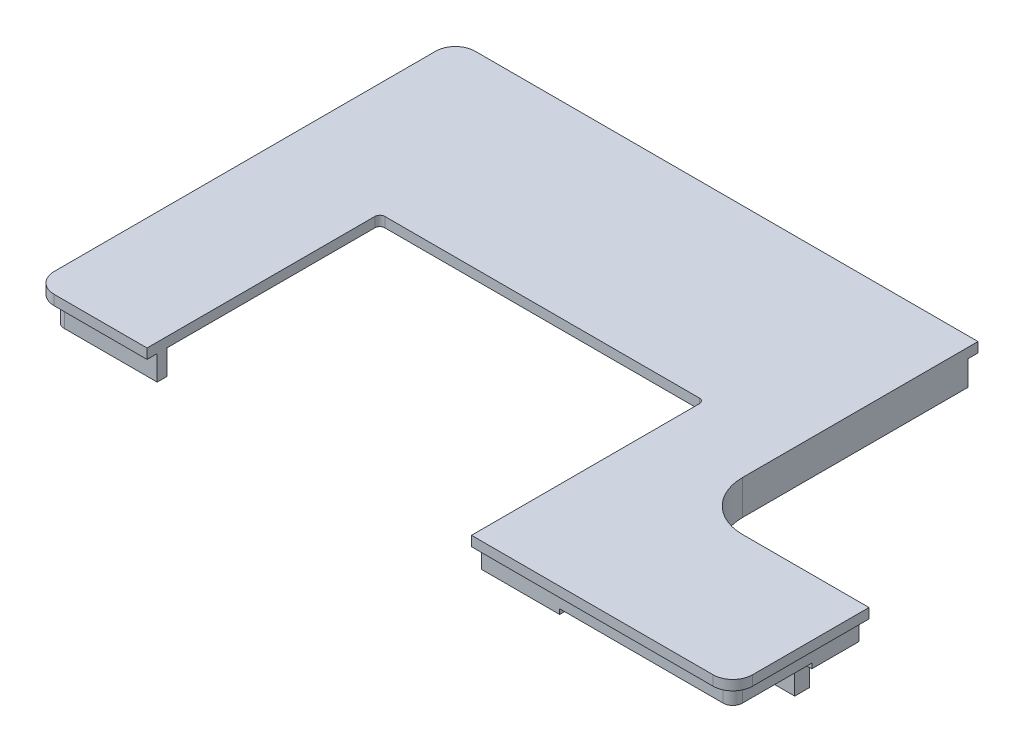
SolidWorks part; units mm, degrees
ref_plane "Plan de face" through (0, 0, 0) normal (0, 0, 1) x (1, 0, 0)
ref_plane "Plan de dessus" through (0, 0, 0) normal (0, 1, 0) x (1, 0, 0)
ref_plane "Plan de droite" through (0, 0, 0) normal (1, 0, 0) x (0, 0, -1)
sketch "Esquisse1" plane through (0, 0, 0) normal (0, 1, 0) x (1, 0, 0)
  line L0 (-70.5, 42.5) -> (-47.5, 42.5)
  line L1 (70.5, -42.5) -> (-70.5, -42.5) construction
  line L2 (70.5, -42.5) -> (70.5, 42.5) construction
  line L3 (70.5, 42.5) -> (-70.5, 42.5) construction
  line L4 (-70.5, -42.5) -> (-70.5, 42.5) construction
  line L5 (70.5, -42.5) -> (-70.5, 42.5) construction
  line L6 (70.5, 42.5) -> (-70.5, -42.5) construction
  line L7 (70.5, 42.5) -> (35, 42.5) construction
  line L8 (70.5, 42.5) -> (70.5, -15) construction
  line L9 (70.5, -15) -> (35, -15) construction
  line L10 (35, 42.5) -> (35, -15) construction
  line L11 (-47.5, 42.5) -> (18, 42.5) construction
  line L18 (18, 42.5) -> (35, 42.5)
  line L19 (35, 42.5) -> (35, -15)
  line L20 (35, -15) -> (70.5, -15)
  line L21 (70.5, -15) -> (70.5, -42.5)
  line L23 (-70.5, -42.5) -> (-70.5, 42.5)
  line L24 (-47.5, 42.5) -> (18, 42.5)
  line L26 (-47.75, -42.5) -> (-47.75, 4.5)
  line L27 (-47.75, 4.5) -> (17.75, 4.5)
  line L28 (17.75, -42.5) -> (17.75, 4.5)
  line L29 (-70.5, -42.5) -> (-47.75, -42.5)
  line L30 (17.75, -42.5) -> (70.5, -42.5)
  point P0 (0, 0)
  dimension "D1" = 141
  dimension "D2" = 85
  dimension "D3" = 57.5
  dimension "D4" = 35.5
  dimension "D8" = 65.5
  dimension "D9" = 22.75
  dimension "D10" = 47
extrude "Boss.-Extru.1" add sketch "Esquisse1" along normal blind 2
fillet "Congé1" radius 10 1 edges at (35, 1, 15)
fillet "Congé3" radius 4 3 edges at (70.5, 1, 42.5) (-70.5, 1, 42.5) (-70.5, 1, -42.5)
fillet "Congé4" radius 1 2 edges at (-47.75, 1, -4.5) (17.75, 1, -4.5)
sketch "Esquisse3" plane through (0, 2, 0) normal (0, 1, 0) x (1, 0, 0)
  line L0 (-68.45, 38.5) -> (-68.45, -38.5)
  line L1 (-66.5, -40.45) -> (-47.75, -40.45)
  line L2 (-47.75, -42.5) -> (-47.75, 3.5) construction
  line L3 (-47.75, -40.45) -> (-47.75, -38.45)
  line L4 (-70.5, 38.5) -> (-70.5, -38.5) construction
  line L6 (-66.5, 40.45) -> (35, 40.45)
  line L7 (35, -5) -> (35, 42.5) construction
  line L8 (70.5, -38.5) -> (70.5, -15) construction
  line L9 (68.45, -15) -> (68.45, -38.5)
  line L10 (66.5, -40.45) -> (17.75, -40.45)
  line L11 (-66.5, -42.5) -> (-47.75, -42.5) construction
  line L12 (17.75, 3.5) -> (17.75, -42.5) construction
  line L13 (17.75, -40.45) -> (17.75, -38.5)
  line L14 (17.75, -38.5) -> (66.5, -38.5)
  line L15 (66.5, -38.5) -> (66.5, -17.05)
  line L16 (66.5, -17.05) -> (45, -17.05)
  line L17 (70.5, -15) -> (45, -15) construction
  line L18 (-47.75, -38.45) -> (-66.5, -38.5)
  line L19 (-66.5, -38.5) -> (-66.5, 38.5)
  line L20 (-66.5, 38.5) -> (32.95, 38.5)
  line L21 (32.95, 38.5) -> (32.95, -5)
  line L22 (68.45, -15) -> (45, -15)
  line L23 (35, -5) -> (35, 40.45)
  arc A1 (-68.45, -38.5) -> (-66.5, -40.45) centre (-66.5, -38.5) ccw
  arc A2 (-66.5, 42.5) -> (-70.5, 38.5) centre (-66.5, 38.5) ccw construction
  arc A3 (-68.45, 38.5) -> (-66.5, 40.45) centre (-66.5, 38.5) cw
  arc A4 (32.95, -5) -> (45, -17.05) centre (45, -5) ccw
  arc A5 (68.45, -38.5) -> (66.5, -40.45) centre (66.5, -38.5) cw
  arc A6 (-70.5, -38.5) -> (-66.5, -42.5) centre (-66.5, -38.5) ccw construction
  arc A7 (35, -5) -> (45, -15) centre (45, -5) ccw construction
  arc A8 (66.5, -42.5) -> (70.5, -38.5) centre (66.5, -38.5) ccw construction
  arc A9 (35, -5) -> (45, -15) centre (45, -5) ccw
  dimension "D4" = 2.05
  dimension "D1" = 2.05
  dimension "D2" = 2
  dimension "D3" = 2.05
  dimension "D5" = 2.05
extrude "Boss.-Extru.2" add sketch "Esquisse3" against normal blind 7
sketch "Esquisse5" plane through (0, -5, 0) normal (0, -1, 0) x (1, 0, 0)
  line L0 (66.5, 40.45) -> (33.5, 40.45)
  line L1 (17.75, 40.45) -> (66.5, 40.45) construction
  line L2 (33.5, 40.45) -> (33.5, 38.5)
  line L3 (66.5, 38.5) -> (17.75, 38.5) construction
  line L4 (33.5, 38.5) -> (66.5, 38.5)
  line L5 (66.5, 38.5) -> (66.5, 24.5)
  line L6 (66.5, 17.05) -> (66.5, 38.5) construction
  line L7 (66.5, 24.5) -> (68.45, 24.5)
  line L8 (68.45, 15) -> (68.45, 38.5) construction
  line L9 (68.45, 24.5) -> (68.45, 38.5)
  arc A0 (68.45, 38.5) -> (66.5, 40.45) centre (66.5, 38.5) ccw construction
  arc A1 (68.45, 38.5) -> (66.5, 40.45) centre (66.5, 38.5) ccw
  dimension "D1" = 33
  dimension "D2" = 14
extrude "Enlèv. mat.-Extru.1" cut sketch "Esquisse5" against normal blind 1
sketch "Esquisse6" plane through (0, 0, 0) normal (0, -1, 0) x (1, 0, 0)
  line L0 (66.5, 38.5) -> (66.5, 17.05) construction
  line L1 (66.5, 26) -> (33.5, 26)
  line L2 (66.5, 26) -> (66.5, 23)
  line L3 (66.5, 23) -> (33.5, 23)
  line L4 (33.5, 26) -> (33.5, 23)
  line L5 (17.75, 42.5) -> (66.5, 42.5) construction
  dimension "D1" = 16.5
  dimension "D2" = 3
  dimension "D3" = 33
extrude "Boss.-Extru.3" add sketch "Esquisse6" along normal blind 10
